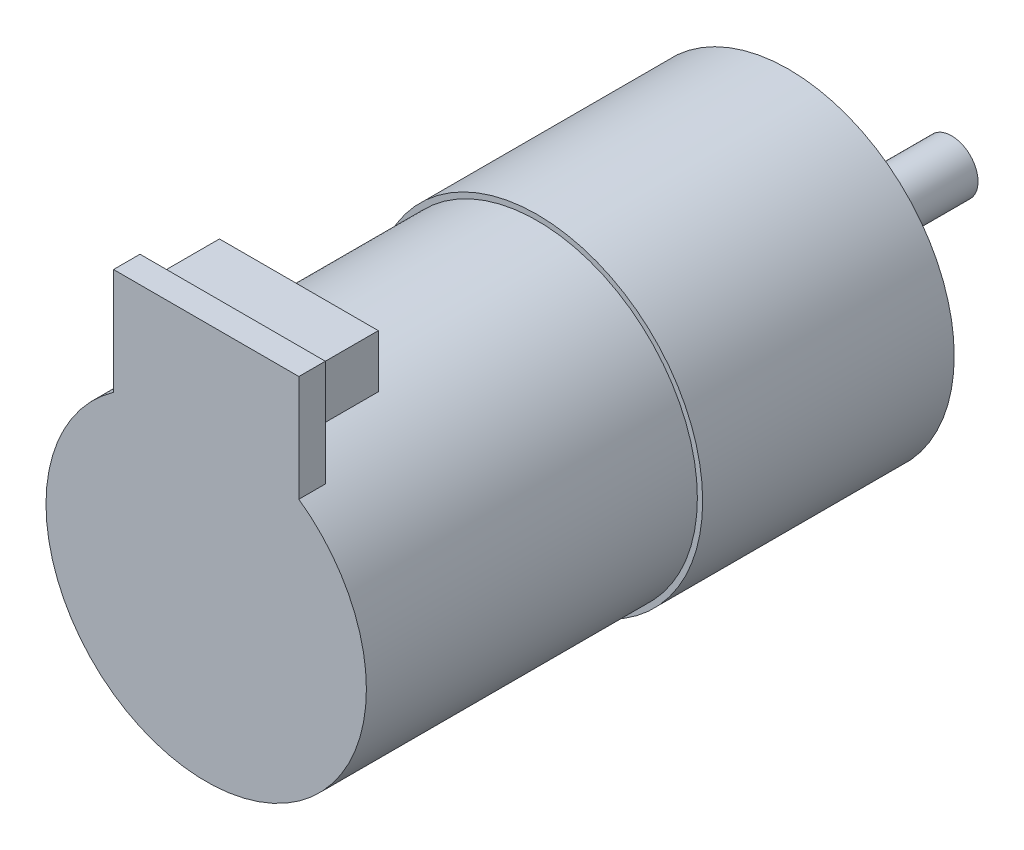
SolidWorks part; units mm, degrees
ref_plane "Front Plane" through (0, 0, 0) normal (0, 0, 1) x (1, 0, 0)
ref_plane "Top Plane" through (0, 0, 0) normal (0, 1, 0) x (1, 0, 0)
ref_plane "Right Plane" through (0, 0, 0) normal (1, 0, 0) x (0, 0, -1)
sketch "Sketch1" plane through (0, 0, 0) normal (0, 0, 1) x (1, 0, 0)
  circle A0 centre (0, 0) radius 12.5
  dimension "D1" = 25
extrude "Boss-Extrude1" add sketch "Sketch1" along normal blind 19
sketch "Sketch2" plane through (0, 0, 19) normal (0, 0, 1) x (1, 0, 0)
  circle A0 centre (0, 0) radius 12.1
  dimension "D1" = 24.2
extrude "Boss-Extrude2" add sketch "Sketch2" along normal blind 23
sketch "Sketch3" plane through (0, 0, 42) normal (0, 0, 1) x (1, 0, 0)
  line L1 (-7, 17.9) -> (7, 17.9)
  line L3 (-7, 17.9) -> (-7, 9.8697)
  line L4 (7, 17.9) -> (7, 9.8697)
  line L5 (0, 0) -> (0, 17.9) construction
  circle A1 centre (0, 0) radius 12.1 construction
  circle A2 centre (0, 0) radius 12.1 construction
  arc A3 (-7, 9.8697) -> (7, 9.8697) centre (0, 0) ccw
  point P1 (0, -12.1)
  dimension "D1" = 17.9
  dimension "D2" = 14
extrude "Boss-Extrude3" add sketch "Sketch3" along normal blind 2
sketch "Sketch4" plane through (0, 0, 42) normal (0, 0, -1) x (-1, 0, 0)
  line L0 (-7, 9.8697) -> (-7, 17.9) construction
  line L2 (-6, 16.9) -> (-6, 12.9)
  line L3 (-6, 12.9) -> (6, 12.9)
  line L4 (6, 16.9) -> (6, 12.9)
  line L6 (-6, 16.9) -> (6, 16.9)
  line L7 (-7, 17.9) -> (7, 17.9) construction
  dimension "D1" = 12
  dimension "D2" = 4
  dimension "D3" = 1
  dimension "D4" = 1
extrude "Boss-Extrude4" add sketch "Sketch4" along normal blind 5
sketch "Sketch5" plane through (0, 0, 0) normal (0, 0, -1) x (-1, 0, 0)
  circle A0 centre (0, 0) radius 3.5
  dimension "D1" = 7
extrude "Boss-Extrude5" add sketch "Sketch5" along normal blind 2.7
sketch "Sketch6" plane through (0, 0, 0) normal (0, 0, -1) x (-1, 0, 0)
  circle A0 centre (0, 0) radius 2
  dimension "D1" = 4
extrude "Boss-Extrude6" add sketch "Sketch6" along normal blind 12.3
sketch "Sketch7" plane through (0, 0, 0) normal (0, 0, -1) x (-1, 0, 0)
  line L0 (0, 0) -> (12.5, 0) construction
  circle A0 centre (0, 0) radius 12.5 construction
  circle A1 centre (10, 0) radius 1.5
  circle A2 centre (-10, 0) radius 1.5
  point P13 (0, 0)
  dimension "D2" = 10
  dimension "D3" = 3
  dimension "D4" = 2
extrude "Cut-Extrude1" cut sketch "Sketch7" against normal blind 5
